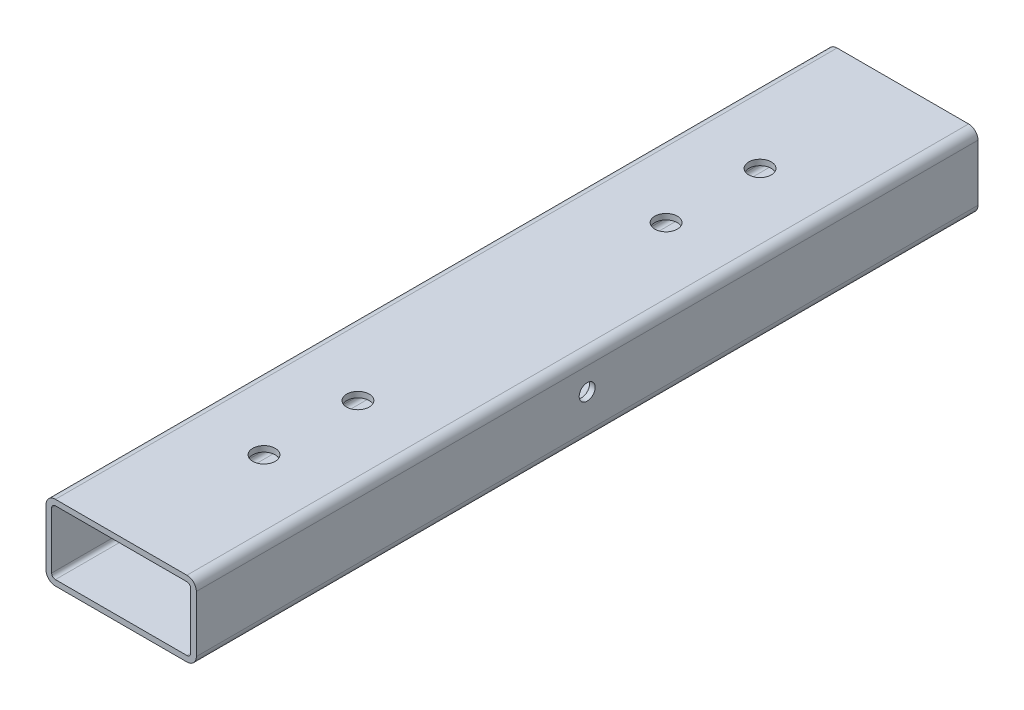
SolidWorks part; units mm, degrees
material "AISI 304"
ref_plane "Спереди" through (0, 0, 0) normal (0, 0, 1) x (1, 0, 0)
ref_plane "Сверху" through (0, 0, 0) normal (0, 1, 0) x (1, 0, 0)
ref_plane "Справа" through (0, 0, 0) normal (1, 0, 0) x (0, 0, -1)
sketch "Эскиз1" plane through (0, 0, 0) normal (0, 0, 1) x (1, 0, 0)
  line L0 (-35, -17) -> (35, -17)
  line L1 (-35, -20) -> (35, -20)
  line L2 (-40, -15) -> (-40, 15)
  line L3 (-35, 20) -> (35, 20)
  line L4 (40, -15) -> (40, 15)
  line L5 (-40, -20) -> (40, 20) construction
  line L6 (-40, 20) -> (40, -20) construction
  line L7 (37, -15) -> (37, 15)
  line L8 (-35, 17) -> (35, 17)
  line L9 (-37, -15) -> (-37, 15)
  arc A0 (35, -20) -> (40, -15) centre (35, -15) ccw
  arc A1 (35, 20) -> (40, 15) centre (35, 15) cw
  arc A2 (-40, 15) -> (-35, 20) centre (-35, 15) cw
  arc A3 (-35, -20) -> (-40, -15) centre (-35, -15) cw
  arc A4 (35, -17) -> (37, -15) centre (35, -15) ccw
  arc A5 (35, 17) -> (37, 15) centre (35, 15) cw
  arc A6 (-37, 15) -> (-35, 17) centre (-35, 15) cw
  arc A7 (-35, -17) -> (-37, -15) centre (-35, -15) cw
  point P0 (0, 0)
  dimension "D2" = 5
  dimension "D1" = 80
  dimension "D4" = 40
  dimension "D3" = 3
extrude "Бобышка-Вытянуть1" add sketch "Эскиз1" along normal mid plane 416
sketch "Эскиз2" plane through (0, 20, 0) normal (0, 1, 0) x (1, 0, 0)
  line L0 (40, -208) -> (40, 208) construction
  line L1 (-40, -208) -> (40, -208)
  line L2 (-40, -208) -> (-40, -148)
  line L3 (-40, -148) -> (40, -148)
  line L4 (40, -208) -> (40, -148)
  line L6 (-40, 208) -> (40, 208)
  line L7 (-40, 208) -> (-40, 148)
  line L8 (-40, 148) -> (40, 148)
  line L9 (40, 208) -> (40, 148)
  dimension "D1" = 60
extrude "Вырез-Вытянуть1" [suppressed] cut sketch "Эскиз2" against normal blind 5
sketch "Эскиз3" plane through (40, 0, 0) normal (1, 0, 0) x (0, 0, -1)
  line L0 (-400, 3) -> (0, 3) construction
  line L1 (0, 3) -> (400, 3) construction
  circle A1 centre (-400, 3) radius 17.8674
  circle A2 centre (0, 3) radius 17.8674
  circle A3 centre (400, 3) radius 17.8674
  dimension "D1" = 400
  dimension "D2" = 400
hole_wizard "Отверстие обработанное метчиком M101" positions "Эскиз4" profile "Эскиз5" tap size "M10" standard "DIN"
sketch "Эскиз4" plane through (40, 0, 0) normal (1, 0, 0) x (0, 0, -1)
  point P3 (400, 3)
  point P6 (0, 3)
  point P9 (-400, 3)
sketch "Эскиз5" plane through (40, 3, -400) normal (0, 1, 0) x (0, 0, -1)
  line L0 (0, 0) -> (0, 30.0537)
  line L1 (0, 30.0537) -> (4.25, 27.5)
  line L2 (4.25, 27.5) -> (4.25, 0)
  line L5 (4.25, 0) -> (0, 0)
  line L10 (0, 30.0537) -> (-4.25, 27.5) construction
  line L11 (0, -6.35) -> (0, 107.95) construction
  dimension "Диаметр сверла" = 8.5
  dimension "Глубина сверла" = 27.5
  dimension "Угол заточки сверла" = 118
cosmetic thread "Отверстие резьбы3" parameters "D1"=20, "D2"=10
sketch "Эскиз6" plane through (0, -20, 0) normal (0, -1, 0) x (1, 0, 0)
  line L0 (-35, 208) -> (35, 208) construction
  circle A0 centre (0, 132) radius 6
  circle A1 centre (0, 82) radius 6
  dimension "D1" = 50
  dimension "D2" = 76
  dimension "D3" = 12
extrude "Вырез-Вытянуть2" cut sketch "Эскиз6" against normal through all both and the other way through all
pattern_linear "Линейный массив1" count 2 spacing 214 along (0, 0, -1) of "Вырез-Вытянуть2"
